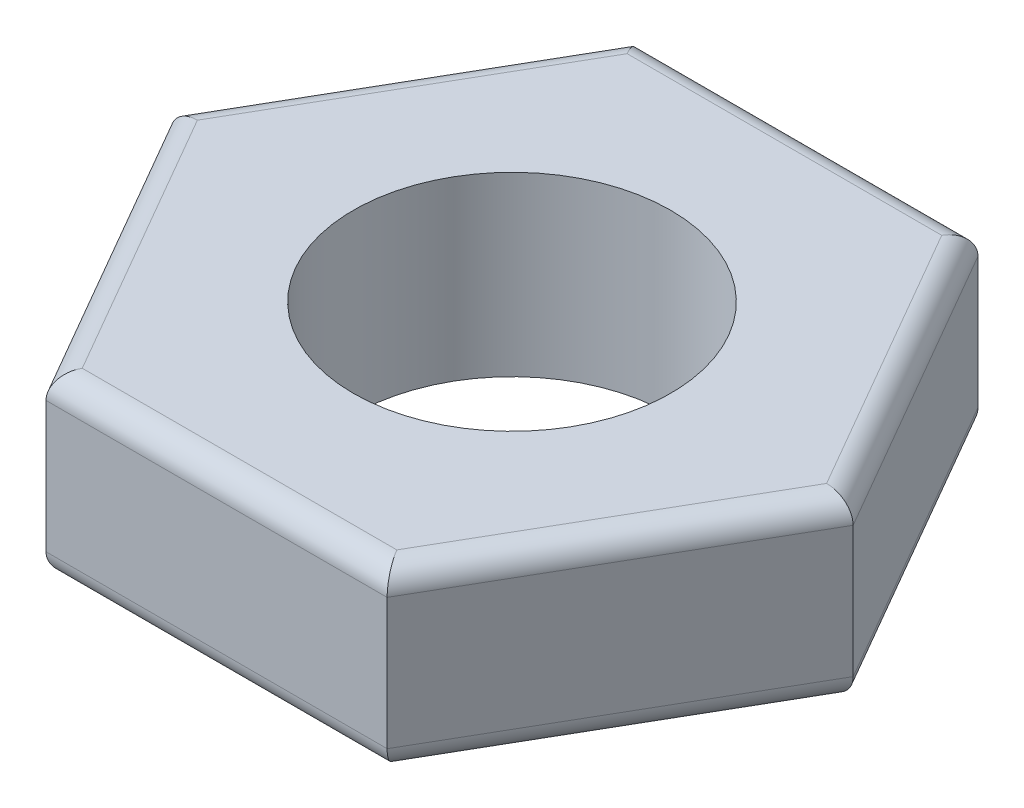
SolidWorks part; units mm, degrees
ref_plane "Front Plane" through (0, 0, 0) normal (0, 0, 1) x (1, 0, 0)
ref_plane "Top Plane" through (0, 0, 0) normal (0, 1, 0) x (1, 0, 0)
ref_plane "Right Plane" through (0, 0, 0) normal (1, 0, 0) x (0, 0, -1)
sketch "Sketch1" plane through (0, 0, 0) normal (0, 1, 0) x (1, 0, 0)
  line L1 (7.419, 0) -> (3.7095, 6.425)
  line L2 (3.7095, 6.425) -> (-3.7095, 6.425)
  line L3 (-3.7095, 6.425) -> (-7.419, 0)
  line L4 (-7.419, 0) -> (-3.7095, -6.425)
  line L5 (-3.7095, -6.425) -> (3.7095, -6.425)
  line L6 (3.7095, -6.425) -> (7.419, 0)
  circle A0 centre (0, 0) radius 3.45
  circle A1 centre (0, 0) radius 6.425 construction
  point P3 (0, 0)
  point P11 (0, 0)
  dimension "D2" = 6.9
  dimension "D1" = 12.85
extrude "Boss-Extrude1" add sketch "Sketch1" along normal blind 3.85
fillet "Fillet1" radius 0.5 12 edges at (-5.5642, 0, 3.2125) (0, 0, 6.425) (5.5642, 0, 3.2125) (5.5642, 0, -3.2125) (0, 0, -6.425) (-5.5642, 0, -3.2125) (0, 3.85, -6.425) (-5.5642, 3.85, -3.2125) (5.5642, 3.85, -3.2125) (5.5642, 3.85, 3.2125) (-5.5642, 3.85, 3.2125) (0, 3.85, 6.425)
